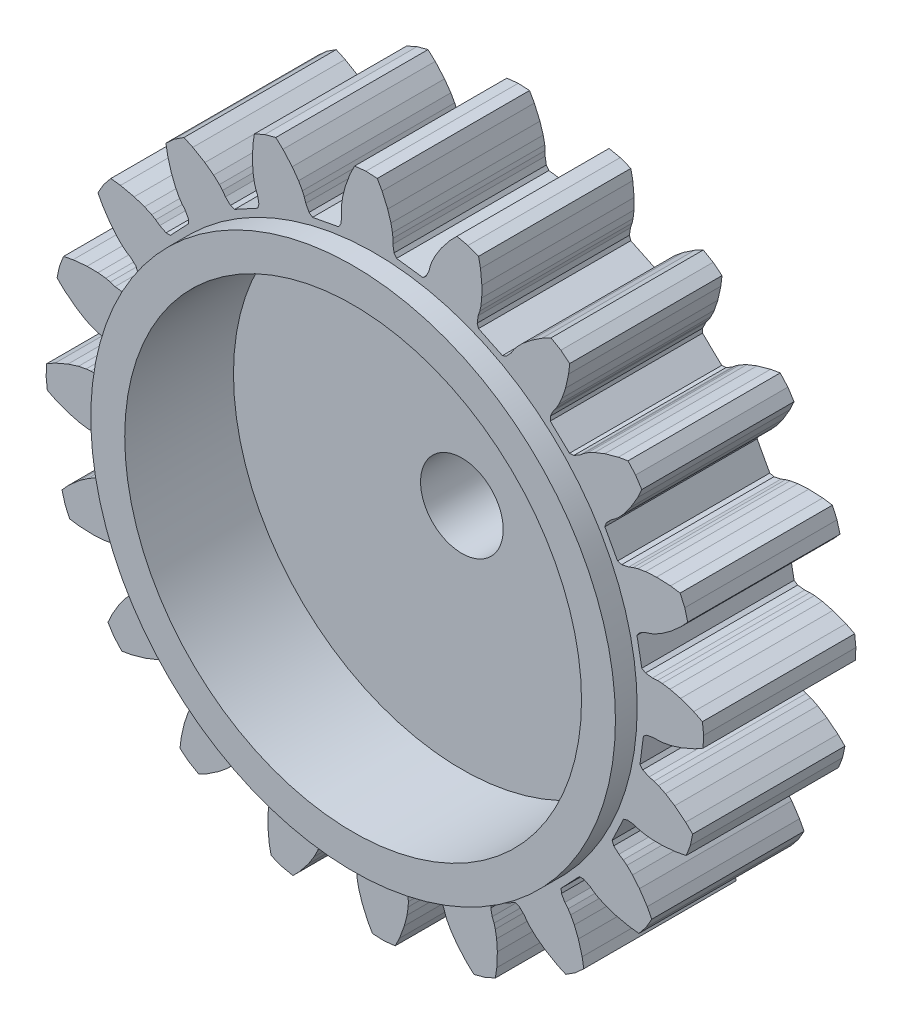
SolidWorks part; units mm, degrees
ref_plane "Front Plane" through (0, 0, 0) normal (0, 0, 1) x (1, 0, 0)
ref_plane "Top Plane" through (0, 0, 0) normal (0, 1, 0) x (1, 0, 0)
ref_plane "Right Plane" through (0, 0, 0) normal (1, 0, 0) x (0, 0, -1)
sketch "Sketch3" plane through (0, 0, 0) normal (0, 0, 1) x (1, 0, 0)
  circle A0 centre (0, 0) radius 10.5
  circle A1 centre (0, 0) radius 12.06
  point P2 (0, 0)
  dimension "D1" = 21
  dimension "D2" = 1.56
extrude "Boss-Extrude1" add sketch "Sketch3" along normal blind 1
sketch "Sketch5" plane through (0, 0, 0) normal (0, 0, 1) x (1, 0, 0)
  circle A2 centre (0, 0) radius 14.1167 construction
  line B0 (12.2724, 1.6677) -> (12.049, 2.8659)
  line B1 (-9.2162, 11.9853) -> (-9.6047, 11.6349)
  line B2 (12.1682, 3.0255) -> (12.454, 3.1759)
  line B3 (14.3139, -4.7677) -> (14.5009, -4.2791)
  line B4 (14.5009, -4.2791) -> (14.6091, -3.7673)
  line B5 (14.6091, -3.7673) -> (14.2881, -3.4538)
  line B6 (14.2881, -3.4538) -> (13.7824, -3.0541)
  line B7 (13.7824, -3.0541) -> (13.3582, -2.7857)
  line B8 (13.3582, -2.7857) -> (13.0363, -2.6264)
  line B9 (13.0363, -2.6264) -> (12.8334, -2.5513)
  line B10 (12.8334, -2.5513) -> (12.6083, -2.4938)
  line B11 (12.6083, -2.4938) -> (12.3147, -2.3592)
  line B12 (12.3147, -2.3592) -> (12.1871, -2.2063)
  line B13 (12.1871, -2.2063) -> (12.3449, -0.9977)
  line B14 (12.3449, -0.9977) -> (12.5076, -0.8828)
  line B15 (12.5076, -0.8828) -> (12.8258, -0.8281)
  line B16 (12.8258, -0.8281) -> (13.0582, -0.8303)
  line B17 (13.0582, -0.8303) -> (13.2736, -0.8098)
  line B18 (13.2736, -0.8098) -> (13.6256, -0.7386)
  line B19 (13.6256, -0.7386) -> (14.1044, -0.5881)
  line B20 (14.1044, -0.5881) -> (14.6959, -0.3317)
  line B21 (14.6959, -0.3317) -> (15.0866, -0.1111)
  line B22 (15.0866, -0.1111) -> (15.1135, 0.4113)
  line B23 (15.1135, 0.4113) -> (15.0583, 0.9315)
  line B24 (15.0583, 0.9315) -> (14.6561, 1.1305)
  line B25 (14.6561, 1.1305) -> (14.0516, 1.3544)
  line B26 (14.0516, 1.3544) -> (13.5653, 1.4786)
  line B27 (13.5653, 1.4786) -> (13.2099, 1.5305)
  line B28 (13.2099, 1.5305) -> (12.9937, 1.5393)
  line B29 (12.9937, 1.5393) -> (12.7618, 1.5244)
  line B30 (12.7618, 1.5244) -> (12.441, 1.5617)
  line B31 (12.441, 1.5617) -> (12.2724, 1.6677)
  line B32 (12.049, 2.8659) -> (12.1682, 3.0255)
  line B33 (12.454, 3.1759) -> (12.6756, 3.2455)
  line B34 (12.6756, 3.2455) -> (12.8742, 3.3316)
  line B35 (12.8742, 3.3316) -> (13.187, 3.5081)
  line B36 (13.187, 3.5081) -> (13.5959, 3.7992)
  line B37 (13.5959, 3.7992) -> (14.0791, 4.2258)
  line B38 (14.0791, 4.2258) -> (14.3826, 4.5563)
  line B39 (14.3826, 4.5563) -> (14.2467, 5.0615)
  line B40 (14.2467, 5.0615) -> (14.0334, 5.5392)
  line B41 (14.0334, 5.5392) -> (13.5894, 5.6042)
  line B42 (13.5894, 5.6042) -> (12.9453, 5.6303)
  line B43 (12.9453, 5.6303) -> (12.4444, 5.5981)
  line B44 (12.4444, 5.5981) -> (12.0904, 5.5377)
  line B45 (12.0904, 5.5377) -> (11.882, 5.4792)
  line B46 (11.882, 5.4792) -> (11.6661, 5.3934)
  line B47 (11.6661, 5.3934) -> (11.3495, 5.3298)
  line B48 (11.3495, 5.3298) -> (11.1564, 5.3784)
  line B49 (11.1564, 5.3784) -> (10.5737, 6.449)
  line B50 (10.5737, 6.449) -> (10.6377, 6.6376)
  line B51 (10.6377, 6.6376) -> (10.863, 6.8689)
  line B52 (10.863, 6.8689) -> (11.0523, 7.0036)
  line B53 (11.0523, 7.0036) -> (11.2145, 7.1469)
  line B54 (11.2145, 7.1469) -> (11.4575, 7.4114)
  line B55 (11.4575, 7.4114) -> (11.7564, 7.8146)
  line B56 (11.7564, 7.8146) -> (12.0842, 8.3697)
  line B57 (12.0842, 8.3697) -> (12.2707, 8.7778)
  line B58 (12.2707, 8.7778) -> (11.9853, 9.2162)
  line B59 (11.9853, 9.2162) -> (11.6349, 9.6047)
  line B60 (11.6349, 9.6047) -> (11.1925, 9.5292)
  line B61 (11.1925, 9.5292) -> (10.5719, 9.355)
  line B62 (10.5719, 9.355) -> (10.1055, 9.1696)
  line B63 (10.1055, 9.1696) -> (9.7874, 9.0028)
  line B64 (9.7874, 9.0028) -> (9.6073, 8.8828)
  line B65 (9.6073, 8.8828) -> (9.4285, 8.7345)
  line B66 (9.4285, 8.7345) -> (9.147, 8.5761)
  line B67 (9.147, 8.5761) -> (8.9483, 8.5627)
  line B68 (8.9483, 8.5627) -> (8.0633, 9.4008)
  line B69 (8.0633, 9.4008) -> (8.0659, 9.5999)
  line B70 (8.0659, 9.5999) -> (8.2087, 9.8896)
  line B71 (8.2087, 9.8896) -> (8.3471, 10.0762)
  line B72 (8.3471, 10.0762) -> (8.4572, 10.2626)
  line B73 (8.4572, 10.2626) -> (8.6064, 10.5892)
  line B74 (8.6064, 10.5892) -> (8.7662, 11.065)
  line B75 (8.7662, 11.065) -> (8.9064, 11.6943)
  line B76 (8.9064, 11.6943) -> (8.9576, 12.14)
  line B77 (8.9576, 12.14) -> (8.5507, 12.4688)
  line B78 (8.5507, 12.4688) -> (8.0974, 12.7299)
  line B79 (8.0974, 12.7299) -> (7.7, 12.5215)
  line B80 (7.7, 12.5215) -> (7.1636, 12.1641)
  line B81 (7.1636, 12.1641) -> (6.7773, 11.8436)
  line B82 (6.7773, 11.8436) -> (6.5263, 11.5867)
  line B83 (6.5263, 11.5867) -> (6.3921, 11.4169)
  line B84 (6.3921, 11.4169) -> (6.2679, 11.2205)
  line B85 (6.2679, 11.2205) -> (6.0492, 10.983)
  line B86 (6.0492, 10.983) -> (5.8643, 10.9088)
  line B87 (5.8643, 10.9088) -> (4.7637, 11.4324)
  line B88 (4.7637, 11.4324) -> (4.7046, 11.6226)
  line B89 (4.7046, 11.6226) -> (4.7509, 11.9422)
  line B90 (4.7509, 11.9422) -> (4.8249, 12.1625)
  line B91 (4.8249, 12.1625) -> (4.8719, 12.3737)
  line B92 (4.8719, 12.3737) -> (4.913, 12.7305)
  line B93 (4.913, 12.7305) -> (4.9179, 13.2324)
  line B94 (4.9179, 13.2324) -> (4.8567, 13.8741)
  line B95 (4.8567, 13.8741) -> (4.7677, 14.3139)
  line B96 (4.7677, 14.3139) -> (4.2791, 14.5009)
  line B97 (4.2791, 14.5009) -> (3.7673, 14.6091)
  line B98 (3.7673, 14.6091) -> (3.4538, 14.2881)
  line B99 (3.4538, 14.2881) -> (3.0541, 13.7824)
  line B100 (3.0541, 13.7824) -> (2.7857, 13.3582)
  line B101 (2.7857, 13.3582) -> (2.6264, 13.0363)
  line B102 (2.6264, 13.0363) -> (2.5513, 12.8334)
  line B103 (2.5513, 12.8334) -> (2.4938, 12.6083)
  line B104 (2.4938, 12.6083) -> (2.3592, 12.3147)
  line B105 (2.3592, 12.3147) -> (2.2063, 12.1871)
  line B106 (2.2063, 12.1871) -> (0.9977, 12.3449)
  line B107 (0.9977, 12.3449) -> (0.8828, 12.5076)
  line B108 (0.8828, 12.5076) -> (0.8281, 12.8258)
  line B109 (0.8281, 12.8258) -> (0.8303, 13.0582)
  line B110 (0.8303, 13.0582) -> (0.8098, 13.2736)
  line B111 (0.8098, 13.2736) -> (0.7386, 13.6256)
  line B112 (0.7386, 13.6256) -> (0.5881, 14.1044)
  line B113 (0.5881, 14.1044) -> (0.3317, 14.6959)
  line B114 (0.3317, 14.6959) -> (0.1111, 15.0866)
  line B115 (0.1111, 15.0866) -> (-0.4113, 15.1135)
  line B116 (-0.4113, 15.1135) -> (-0.9315, 15.0583)
  line B117 (-0.9315, 15.0583) -> (-1.1305, 14.6561)
  line B118 (-1.1305, 14.6561) -> (-1.3544, 14.0516)
  line B119 (-1.3544, 14.0516) -> (-1.4786, 13.5653)
  line B120 (-1.4786, 13.5653) -> (-1.5305, 13.2099)
  line B121 (-1.5305, 13.2099) -> (-1.5393, 12.9937)
  line B122 (-1.5393, 12.9937) -> (-1.5244, 12.7618)
  line B123 (-1.5244, 12.7618) -> (-1.5617, 12.441)
  line B124 (-1.5617, 12.441) -> (-1.6677, 12.2724)
  line B125 (-1.6677, 12.2724) -> (-2.8659, 12.049)
  line B126 (-2.8659, 12.049) -> (-3.0255, 12.1682)
  line B127 (-3.0255, 12.1682) -> (-3.1759, 12.454)
  line B128 (-3.1759, 12.454) -> (-3.2455, 12.6756)
  line B129 (-3.2455, 12.6756) -> (-3.3316, 12.8742)
  line B130 (-3.3316, 12.8742) -> (-3.5081, 13.187)
  line B131 (-3.5081, 13.187) -> (-3.7992, 13.5959)
  line B132 (-3.7992, 13.5959) -> (-4.2258, 14.0791)
  line B133 (-4.2258, 14.0791) -> (-4.5563, 14.3826)
  line B134 (-4.5563, 14.3826) -> (-5.0615, 14.2467)
  line B135 (-5.0615, 14.2467) -> (-5.5392, 14.0334)
  line B136 (-5.5392, 14.0334) -> (-5.6042, 13.5894)
  line B137 (-5.6042, 13.5894) -> (-5.6303, 12.9453)
  line B138 (-5.6303, 12.9453) -> (-5.5981, 12.4444)
  line B139 (-5.5981, 12.4444) -> (-5.5377, 12.0904)
  line B140 (-5.5377, 12.0904) -> (-5.4792, 11.882)
  line B141 (-5.4792, 11.882) -> (-5.3934, 11.6661)
  line B142 (-5.3934, 11.6661) -> (-5.3298, 11.3495)
  line B143 (-5.3298, 11.3495) -> (-5.3784, 11.1564)
  line B144 (-5.3784, 11.1564) -> (-6.449, 10.5737)
  line B145 (-6.449, 10.5737) -> (-6.6376, 10.6377)
  line B146 (-6.6376, 10.6377) -> (-6.8689, 10.863)
  line B147 (-6.8689, 10.863) -> (-7.0036, 11.0523)
  line B148 (-7.0036, 11.0523) -> (-7.1469, 11.2145)
  line B149 (-7.1469, 11.2145) -> (-7.4114, 11.4575)
  line B150 (-7.4114, 11.4575) -> (-7.8146, 11.7564)
  line B151 (-7.8146, 11.7564) -> (-8.3697, 12.0842)
  line B152 (-8.3697, 12.0842) -> (-8.7778, 12.2707)
  line B153 (-8.7778, 12.2707) -> (-9.2162, 11.9853)
  line B154 (-9.6047, 11.6349) -> (-9.5292, 11.1925)
  line B155 (-9.5292, 11.1925) -> (-9.355, 10.5719)
  line B156 (-9.355, 10.5719) -> (-9.1696, 10.1055)
  line B157 (-9.1696, 10.1055) -> (-9.0028, 9.7874)
  line B158 (-9.0028, 9.7874) -> (-8.8828, 9.6073)
  line B159 (-8.8828, 9.6073) -> (-8.7345, 9.4285)
  line B160 (-8.7345, 9.4285) -> (-8.5761, 9.147)
  line B161 (-8.5761, 9.147) -> (-8.5627, 8.9483)
  line B162 (-8.5627, 8.9483) -> (-9.4008, 8.0633)
  line B163 (-9.4008, 8.0633) -> (-9.5999, 8.0659)
  line B164 (-9.5999, 8.0659) -> (-9.8896, 8.2087)
  line B165 (-9.8896, 8.2087) -> (-10.0762, 8.3471)
  line B166 (-10.0762, 8.3471) -> (-10.2626, 8.4572)
  line B167 (-10.2626, 8.4572) -> (-10.5892, 8.6064)
  line B168 (-10.5892, 8.6064) -> (-11.065, 8.7662)
  line B169 (-11.065, 8.7662) -> (-11.6943, 8.9064)
  line B170 (-11.6943, 8.9064) -> (-12.14, 8.9576)
  line B171 (-12.14, 8.9576) -> (-12.4688, 8.5507)
  line B172 (-12.4688, 8.5507) -> (-12.7299, 8.0974)
  line B173 (-12.7299, 8.0974) -> (-12.5215, 7.7)
  line B174 (-12.5215, 7.7) -> (-12.1641, 7.1636)
  line B175 (-12.1641, 7.1636) -> (-11.8436, 6.7773)
  line B176 (-11.8436, 6.7773) -> (-11.5867, 6.5263)
  line B177 (-11.5867, 6.5263) -> (-11.4169, 6.3921)
  line B178 (-11.4169, 6.3921) -> (-11.2205, 6.2679)
  line B179 (-11.2205, 6.2679) -> (-10.983, 6.0492)
  line B180 (-10.983, 6.0492) -> (-10.9088, 5.8643)
  line B181 (-10.9088, 5.8643) -> (-11.4324, 4.7637)
  line B182 (-11.4324, 4.7637) -> (-11.6226, 4.7046)
  line B183 (-11.6226, 4.7046) -> (-11.9422, 4.7509)
  line B184 (-11.9422, 4.7509) -> (-12.1625, 4.8249)
  line B185 (-12.1625, 4.8249) -> (-12.3737, 4.8719)
  line B186 (-12.3737, 4.8719) -> (-12.7305, 4.913)
  line B187 (-12.7305, 4.913) -> (-13.2324, 4.9179)
  line B188 (-13.2324, 4.9179) -> (-13.8741, 4.8567)
  line B189 (-13.8741, 4.8567) -> (-14.3139, 4.7677)
  line B190 (-14.3139, 4.7677) -> (-14.5009, 4.2791)
  line B191 (-14.5009, 4.2791) -> (-14.6091, 3.7673)
  line B192 (-14.6091, 3.7673) -> (-14.2881, 3.4538)
  line B193 (-14.2881, 3.4538) -> (-13.7824, 3.0541)
  line B194 (-13.7824, 3.0541) -> (-13.3582, 2.7857)
  line B195 (-13.3582, 2.7857) -> (-13.0363, 2.6264)
  line B196 (-13.0363, 2.6264) -> (-12.8334, 2.5513)
  line B197 (-12.8334, 2.5513) -> (-12.6083, 2.4938)
  line B198 (-12.6083, 2.4938) -> (-12.3147, 2.3592)
  line B199 (-12.3147, 2.3592) -> (-12.1871, 2.2063)
  line B200 (-12.1871, 2.2063) -> (-12.3449, 0.9977)
  line B201 (-12.3449, 0.9977) -> (-12.5076, 0.8828)
  line B202 (-12.5076, 0.8828) -> (-12.8258, 0.8281)
  line B203 (-12.8258, 0.8281) -> (-13.0582, 0.8303)
  line B204 (-13.0582, 0.8303) -> (-13.2736, 0.8098)
  line B205 (-13.2736, 0.8098) -> (-13.6256, 0.7386)
  line B206 (-13.6256, 0.7386) -> (-14.1044, 0.5881)
  line B207 (-14.1044, 0.5881) -> (-14.6959, 0.3317)
  line B208 (-14.6959, 0.3317) -> (-15.0866, 0.1111)
  line B209 (-15.0866, 0.1111) -> (-15.1135, -0.4113)
  line B210 (-15.1135, -0.4113) -> (-15.0583, -0.9315)
  line B211 (-15.0583, -0.9315) -> (-14.6561, -1.1305)
  line B212 (-14.6561, -1.1305) -> (-14.0516, -1.3544)
  line B213 (-14.0516, -1.3544) -> (-13.5653, -1.4786)
  line B214 (-13.5653, -1.4786) -> (-13.2099, -1.5305)
  line B215 (-13.2099, -1.5305) -> (-12.9937, -1.5393)
  line B216 (-12.9937, -1.5393) -> (-12.7618, -1.5244)
  line B217 (-12.7618, -1.5244) -> (-12.441, -1.5617)
  line B218 (-12.441, -1.5617) -> (-12.2724, -1.6677)
  line B219 (-12.2724, -1.6677) -> (-12.049, -2.8659)
  line B220 (-12.049, -2.8659) -> (-12.1682, -3.0255)
  line B221 (-12.1682, -3.0255) -> (-12.454, -3.1759)
  line B222 (-12.454, -3.1759) -> (-12.6756, -3.2455)
  line B223 (-12.6756, -3.2455) -> (-12.8742, -3.3316)
  line B224 (-12.8742, -3.3316) -> (-13.187, -3.5081)
  line B225 (-13.187, -3.5081) -> (-13.5959, -3.7992)
  line B226 (-13.5959, -3.7992) -> (-14.0791, -4.2258)
  line B227 (-14.0791, -4.2258) -> (-14.3826, -4.5563)
  line B228 (-14.3826, -4.5563) -> (-14.2467, -5.0615)
  line B229 (-14.2467, -5.0615) -> (-14.0334, -5.5392)
  line B230 (-14.0334, -5.5392) -> (-13.5894, -5.6042)
  line B231 (-13.5894, -5.6042) -> (-12.9453, -5.6303)
  line B232 (-12.9453, -5.6303) -> (-12.4444, -5.5981)
  line B233 (-12.4444, -5.5981) -> (-12.0904, -5.5377)
  line B234 (-12.0904, -5.5377) -> (-11.882, -5.4792)
  line B235 (-11.882, -5.4792) -> (-11.6661, -5.3934)
  line B236 (-11.6661, -5.3934) -> (-11.3495, -5.3298)
  line B237 (-11.3495, -5.3298) -> (-11.1564, -5.3784)
  line B238 (-11.1564, -5.3784) -> (-10.5737, -6.449)
  line B239 (-10.5737, -6.449) -> (-10.6377, -6.6376)
  line B240 (-10.6377, -6.6376) -> (-10.863, -6.8689)
  line B241 (-10.863, -6.8689) -> (-11.0523, -7.0036)
  line B242 (-11.0523, -7.0036) -> (-11.2145, -7.1469)
  line B243 (-11.2145, -7.1469) -> (-11.4575, -7.4114)
  line B244 (-11.4575, -7.4114) -> (-11.7564, -7.8146)
  line B245 (-11.7564, -7.8146) -> (-12.0842, -8.3697)
  line B246 (-12.0842, -8.3697) -> (-12.2707, -8.7778)
  line B247 (-12.2707, -8.7778) -> (-11.9853, -9.2162)
  line B248 (-11.9853, -9.2162) -> (-11.6349, -9.6047)
  line B249 (-11.6349, -9.6047) -> (-11.1925, -9.5292)
  line B250 (-11.1925, -9.5292) -> (-10.5719, -9.355)
  line B251 (-10.5719, -9.355) -> (-10.1055, -9.1696)
  line B252 (-10.1055, -9.1696) -> (-9.7874, -9.0028)
  line B253 (-9.7874, -9.0028) -> (-9.6073, -8.8828)
  line B254 (-9.6073, -8.8828) -> (-9.4285, -8.7345)
  line B255 (-9.4285, -8.7345) -> (-9.147, -8.5761)
  line B256 (-9.147, -8.5761) -> (-8.9483, -8.5627)
  line B257 (-8.9483, -8.5627) -> (-8.0633, -9.4008)
  line B258 (-8.0633, -9.4008) -> (-8.0659, -9.5999)
  line B259 (-8.0659, -9.5999) -> (-8.2087, -9.8896)
  line B260 (-8.2087, -9.8896) -> (-8.3471, -10.0762)
  line B261 (-8.3471, -10.0762) -> (-8.4572, -10.2626)
  line B262 (-8.4572, -10.2626) -> (-8.6064, -10.5892)
  line B263 (-8.6064, -10.5892) -> (-8.7662, -11.065)
  line B264 (-8.7662, -11.065) -> (-8.9064, -11.6943)
  line B265 (-8.9064, -11.6943) -> (-8.9576, -12.14)
  line B266 (-8.9576, -12.14) -> (-8.5507, -12.4688)
  line B267 (-8.5507, -12.4688) -> (-8.0974, -12.7299)
  line B268 (-8.0974, -12.7299) -> (-7.7, -12.5215)
  line B269 (-7.7, -12.5215) -> (-7.1636, -12.1641)
  line B270 (-7.1636, -12.1641) -> (-6.7773, -11.8436)
  line B271 (-6.7773, -11.8436) -> (-6.5263, -11.5867)
  line B272 (-6.5263, -11.5867) -> (-6.3921, -11.4169)
  line B273 (-6.3921, -11.4169) -> (-6.2679, -11.2205)
  line B274 (-6.2679, -11.2205) -> (-6.0492, -10.983)
  line B275 (-6.0492, -10.983) -> (-5.8643, -10.9088)
  line B276 (-5.8643, -10.9088) -> (-4.7637, -11.4324)
  line B277 (-4.7637, -11.4324) -> (-4.7046, -11.6226)
  line B278 (-4.7046, -11.6226) -> (-4.7509, -11.9422)
  line B279 (-4.7509, -11.9422) -> (-4.8249, -12.1625)
  line B280 (-4.8249, -12.1625) -> (-4.8719, -12.3737)
  line B281 (-4.8719, -12.3737) -> (-4.913, -12.7305)
  line B282 (-4.913, -12.7305) -> (-4.9179, -13.2324)
  line B283 (-4.9179, -13.2324) -> (-4.8567, -13.8741)
  line B284 (-4.8567, -13.8741) -> (-4.7677, -14.3139)
  line B285 (-4.7677, -14.3139) -> (-4.2791, -14.5009)
  line B286 (-4.2791, -14.5009) -> (-3.7673, -14.6091)
  line B287 (-3.7673, -14.6091) -> (-3.4538, -14.2881)
  line B288 (-3.4538, -14.2881) -> (-3.0541, -13.7824)
  line B289 (-3.0541, -13.7824) -> (-2.7857, -13.3582)
  line B290 (-2.7857, -13.3582) -> (-2.6264, -13.0363)
  line B291 (-2.6264, -13.0363) -> (-2.5513, -12.8334)
  line B292 (-2.5513, -12.8334) -> (-2.4938, -12.6083)
  line B293 (-2.4938, -12.6083) -> (-2.3592, -12.3147)
  line B294 (-2.3592, -12.3147) -> (-2.2063, -12.1871)
  line B295 (-2.2063, -12.1871) -> (-0.9977, -12.3449)
  line B296 (-0.9977, -12.3449) -> (-0.8828, -12.5076)
  line B297 (-0.8828, -12.5076) -> (-0.8281, -12.8258)
  line B298 (-0.8281, -12.8258) -> (-0.8303, -13.0582)
  line B299 (-0.8303, -13.0582) -> (-0.8098, -13.2736)
  line B300 (-0.8098, -13.2736) -> (-0.7386, -13.6256)
  line B301 (-0.7386, -13.6256) -> (-0.5881, -14.1044)
  line B302 (-0.5881, -14.1044) -> (-0.3317, -14.6959)
  line B303 (-0.3317, -14.6959) -> (-0.1111, -15.0866)
  line B304 (-0.1111, -15.0866) -> (0.4113, -15.1135)
  line B305 (0.4113, -15.1135) -> (0.9315, -15.0583)
  line B306 (0.9315, -15.0583) -> (1.1305, -14.6561)
  line B307 (1.1305, -14.6561) -> (1.3544, -14.0516)
  line B308 (1.3544, -14.0516) -> (1.4786, -13.5653)
  line B309 (1.4786, -13.5653) -> (1.5305, -13.2099)
  line B310 (1.5305, -13.2099) -> (1.5393, -12.9937)
  line B311 (1.5393, -12.9937) -> (1.5244, -12.7618)
  line B312 (1.5244, -12.7618) -> (1.5617, -12.441)
  line B313 (1.5617, -12.441) -> (1.6677, -12.2724)
  line B314 (1.6677, -12.2724) -> (2.8659, -12.049)
  line B315 (2.8659, -12.049) -> (3.0255, -12.1682)
  line B316 (3.0255, -12.1682) -> (3.1759, -12.454)
  line B317 (3.1759, -12.454) -> (3.2455, -12.6756)
  line B318 (3.2455, -12.6756) -> (3.3316, -12.8742)
  line B319 (3.3316, -12.8742) -> (3.5081, -13.187)
  line B320 (3.5081, -13.187) -> (3.7992, -13.5959)
  line B321 (3.7992, -13.5959) -> (4.2258, -14.0791)
  line B322 (4.2258, -14.0791) -> (4.5563, -14.3826)
  line B323 (4.5563, -14.3826) -> (5.0615, -14.2467)
  line B324 (5.0615, -14.2467) -> (5.5392, -14.0334)
  line B325 (5.5392, -14.0334) -> (5.6042, -13.5894)
  line B326 (5.6042, -13.5894) -> (5.6303, -12.9453)
  line B327 (5.6303, -12.9453) -> (5.5981, -12.4444)
  line B328 (5.5981, -12.4444) -> (5.5377, -12.0904)
  line B329 (5.5377, -12.0904) -> (5.4792, -11.882)
  line B330 (5.4792, -11.882) -> (5.3934, -11.6661)
  line B331 (5.3934, -11.6661) -> (5.3298, -11.3495)
  line B332 (5.3298, -11.3495) -> (5.3784, -11.1564)
  line B333 (5.3784, -11.1564) -> (6.449, -10.5737)
  line B334 (6.449, -10.5737) -> (6.6376, -10.6377)
  line B335 (6.6376, -10.6377) -> (6.8689, -10.863)
  line B336 (6.8689, -10.863) -> (7.0036, -11.0523)
  line B337 (7.0036, -11.0523) -> (7.1469, -11.2145)
  line B338 (7.1469, -11.2145) -> (7.4114, -11.4575)
  line B339 (7.4114, -11.4575) -> (7.8146, -11.7564)
  line B340 (7.8146, -11.7564) -> (8.3697, -12.0842)
  line B341 (8.3697, -12.0842) -> (8.7778, -12.2707)
  line B342 (8.7778, -12.2707) -> (9.2162, -11.9853)
  line B343 (9.2162, -11.9853) -> (9.6047, -11.6349)
  line B344 (9.6047, -11.6349) -> (9.5292, -11.1925)
  line B345 (9.5292, -11.1925) -> (9.355, -10.5719)
  line B346 (9.355, -10.5719) -> (9.1696, -10.1055)
  line B347 (9.1696, -10.1055) -> (9.0028, -9.7874)
  line B348 (9.0028, -9.7874) -> (8.8828, -9.6073)
  line B349 (8.8828, -9.6073) -> (8.7345, -9.4285)
  line B350 (8.7345, -9.4285) -> (8.5761, -9.147)
  line B351 (8.5761, -9.147) -> (8.5627, -8.9483)
  line B352 (8.5627, -8.9483) -> (9.4008, -8.0633)
  line B353 (9.4008, -8.0633) -> (9.5999, -8.0659)
  line B354 (9.5999, -8.0659) -> (9.8896, -8.2087)
  line B355 (9.8896, -8.2087) -> (10.0762, -8.3471)
  line B356 (10.0762, -8.3471) -> (10.2626, -8.4572)
  line B357 (10.2626, -8.4572) -> (10.5892, -8.6064)
  line B358 (10.5892, -8.6064) -> (11.065, -8.7662)
  line B359 (11.065, -8.7662) -> (11.6943, -8.9064)
  line B360 (11.6943, -8.9064) -> (12.14, -8.9576)
  line B361 (12.14, -8.9576) -> (12.4688, -8.5507)
  line B362 (12.4688, -8.5507) -> (12.7299, -8.0974)
  line B363 (12.7299, -8.0974) -> (12.5215, -7.7)
  line B364 (12.5215, -7.7) -> (12.1641, -7.1636)
  line B365 (12.1641, -7.1636) -> (11.8436, -6.7773)
  line B366 (11.8436, -6.7773) -> (11.5867, -6.5263)
  line B367 (11.5867, -6.5263) -> (11.4169, -6.3921)
  line B368 (11.4169, -6.3921) -> (11.2205, -6.2679)
  line B369 (11.2205, -6.2679) -> (10.983, -6.0492)
  line B370 (10.983, -6.0492) -> (10.9088, -5.8643)
  line B371 (10.9088, -5.8643) -> (11.4324, -4.7637)
  line B372 (11.4324, -4.7637) -> (11.6226, -4.7046)
  line B373 (11.6226, -4.7046) -> (11.9422, -4.7509)
  line B374 (11.9422, -4.7509) -> (12.1625, -4.8249)
  line B375 (12.1625, -4.8249) -> (12.3737, -4.8719)
  line B376 (12.3737, -4.8719) -> (12.7305, -4.913)
  line B377 (12.7305, -4.913) -> (13.2324, -4.9179)
  line B378 (13.2324, -4.9179) -> (13.8741, -4.8567)
  line B379 (13.8741, -4.8567) -> (14.3139, -4.7677)
sketch_block_instance "InvoluteGear_1 (3)-1"
sketch_block "InvoluteGear_1 (3)"
extrude "Boss-Extrude2" add sketch "Sketch5" against normal blind 7
sketch "Sketch7" plane through (0, 0, -7) normal (0, 0, -1) x (-1, 0, 0)
  circle A1 centre (0, 0) radius 14.0996 construction
sketch "Sketch8" plane through (0, 0, 0) normal (0, 0, 1) x (1, 0, 0)
  circle A1 centre (0, 0) radius 10.5
  circle A2 centre (0, 0) radius 10.5
  dimension "D1" = 0
sketch "Sketch6" plane through (0, 0, 0) normal (0, 0, 1) x (1, 0, 0)
  circle A0 centre (0, 0) radius 1.9
  dimension "D1" = 3.8
extrude "Cut-Extrude1" cut sketch "Sketch6" along normal through all both and the other way through all
extrude "Cut-Extrude2" cut sketch "Sketch8" against normal blind 4
